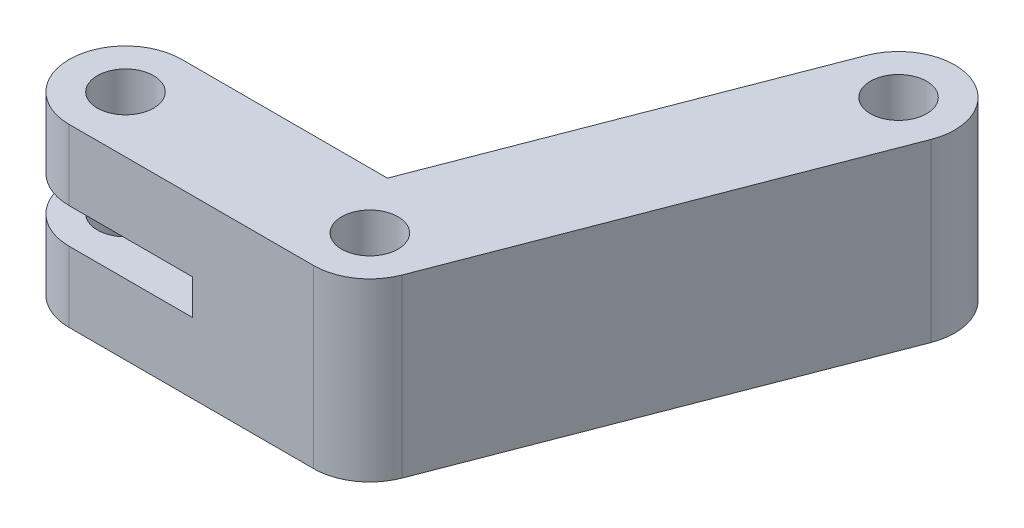
SolidWorks part; units mm, degrees
ref_plane "Front Plane" through (0, 0, 0) normal (0, 0, 1) x (1, 0, 0)
ref_plane "Top Plane" through (0, 0, 0) normal (0, 1, 0) x (1, 0, 0)
ref_plane "Right Plane" through (0, 0, 0) normal (1, 0, 0) x (0, 0, -1)
sketch "Sketch1" plane through (0, 0, 0) normal (0, 1, 0) x (1, 0, 0)
  line L0 (-37.4962, 0) -> (38.5028, 0) construction
  line L1 (0, 0) -> (20.89, 54.24) construction
  line L2 (-34.72, 0) -> (0, 0) construction
  line L3 (-34.72, 8) -> (0, 8)
  line L4 (-34.72, -8) -> (0, -8)
  line L5 (0, 0) -> (20.89, 54.24) construction
  line L6 (-7.4655, 2.8752) -> (13.4245, 57.1152)
  line L7 (7.4655, -2.8752) -> (28.3555, 51.3648)
  circle A0 centre (0, 0) radius 4
  circle A1 centre (-34.72, 0) radius 4
  circle A2 centre (20.89, 54.24) radius 4
  arc A3 (-34.72, 8) -> (-34.72, -8) centre (-34.72, 0) ccw
  arc A4 (0, -8) -> (0, 8) centre (0, 0) ccw
  arc A5 (-7.4655, 2.8752) -> (7.4655, -2.8752) centre (0, 0) ccw
  arc A6 (28.3555, 51.3648) -> (13.4245, 57.1152) centre (20.89, 54.24) ccw
  point P9 (-17.36, 0)
  point P14 (10.445, 27.12)
  dimension "D4" = 8
  dimension "D5" = 8
  dimension "D6" = 8
  dimension "D1" = 34.72
  dimension "D2" = 20.89
  dimension "D3" = 54.24
extrude "Boss-Extrude1" add sketch "Sketch1" along normal mid plane 25 contours L7 A6 L6 A5 | L4 A4 L3 A3 | A1 | A0 | A2
sketch "Sketch4" plane through (0, 0, 8) normal (0, 0, 1) x (1, 0, 0)
  line L0 (-42.72, 2.5) -> (-17.22, 2.5)
  line L1 (-42.72, 12.5) -> (-42.72, -12.5) construction
  line L2 (-17.22, 2.5) -> (-17.22, -2.5)
  line L3 (-17.22, -2.5) -> (-42.72, -2.5)
  line L4 (-42.72, -2.5) -> (-42.72, 2.5)
  dimension "D1" = 25.5
  dimension "D2" = 2.5
  dimension "D3" = 2.5
extrude "Cut-Extrude1" cut sketch "Sketch4" against normal up to next
sketch "Sketch5" plane through (0, 12.5, 0) normal (0, 1, 0) x (1, 0, 0)
  circle A0 centre (0, 0) radius 4
  dimension "D1" = 8
extrude "Cut-Extrude2" cut sketch "Sketch5" against normal through all
